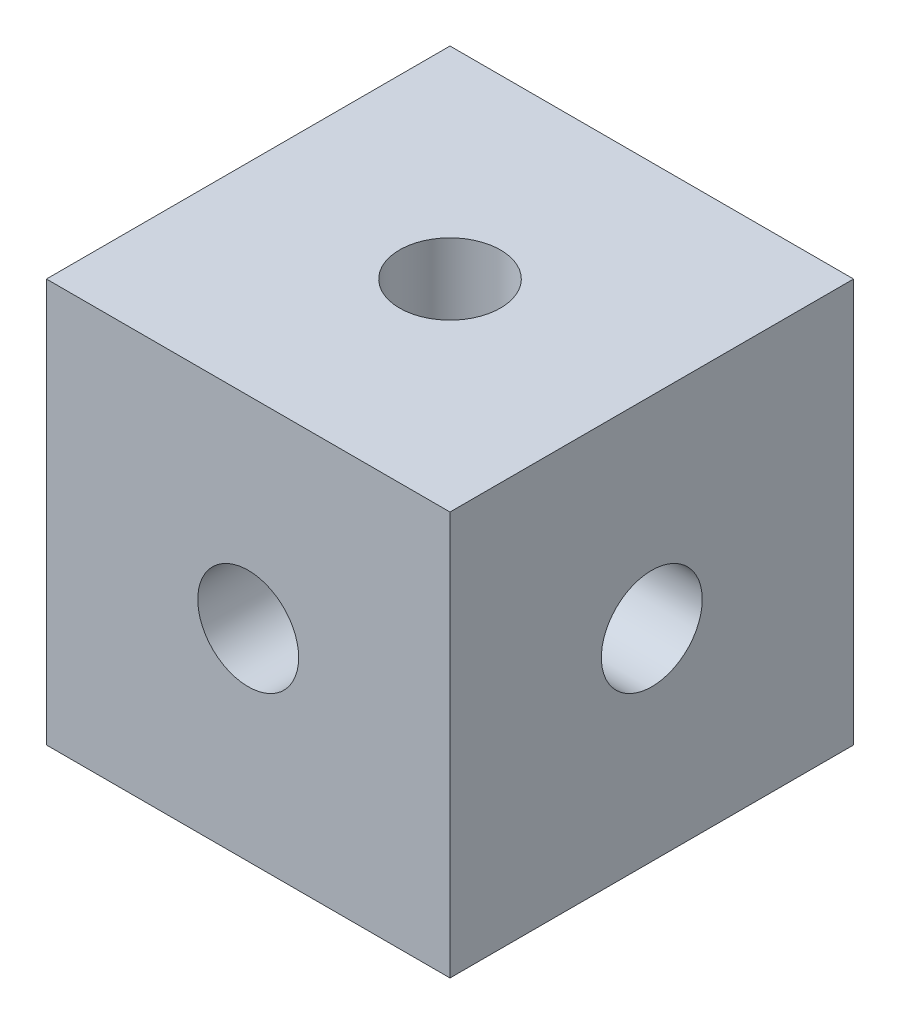
SolidWorks part; units mm, degrees
material "5052-H32"
ref_plane "前视基准面" through (0, 0, 0) normal (0, 0, 1) x (1, 0, 0)
ref_plane "上视基准面" through (0, 0, 0) normal (0, 1, 0) x (1, 0, 0)
ref_plane "右视基准面" through (0, 0, 0) normal (1, 0, 0) x (0, 0, -1)
other "Configuration Table"
sketch "草图1" plane through (0, 0, 0) normal (0, 1, 0) x (1, 0, 0)
  line L1 (-5, 5) -> (5, 5)
  line L2 (-5, 5) -> (-5, -5)
  line L3 (-5, -5) -> (5, -5)
  line L4 (5, 5) -> (5, -5)
  line L5 (-5, 5) -> (5, -5) construction
  line L6 (-5, -5) -> (5, 5) construction
  point P0 (0, 0)
  dimension "D1" = 10
extrude "凸台-拉伸1" add sketch "草图1" along normal mid plane 10
hole_wizard " 螺纹孔1" positions "草图2" profile "草图3" tap size "M3" standard "GB" end condition through all
sketch "草图2" plane through (0, 5, 0) normal (0, 1, 0) x (1, 0, 0)
  point P0 (0, 0)
sketch "草图3" plane through (0, 5, 0) normal (1, 0, 0) x (0, 0, 1)
  line L0 (0, 0) -> (0, 10)
  line L1 (0, 10) -> (1.25, 10)
  line L2 (1.25, 10) -> (1.25, 0)
  line L5 (1.25, 0) -> (0, 0)
  line L11 (0, -6.35) -> (0, 107.95) construction
  dimension "通孔螺纹孔钻头直径" = 2.5
  dimension "通孔螺纹孔钻头深度" = 10
cosmetic thread "孔螺蚊线1" parameters "D2"=3
hole_wizard " 螺纹孔2" positions "草图4" profile "草图5" tap size "M3" standard "GB" end condition through all
sketch "草图4" plane through (5, 0, 0) normal (1, 0, 0) x (0, 0, -1)
  point P0 (0, 0)
sketch "草图5" plane through (5, 0, 0) normal (0, 1, 0) x (0, 0, -1)
  line L0 (0, 0) -> (0, 10)
  line L1 (0, 10) -> (1.25, 10)
  line L2 (1.25, 10) -> (1.25, 0)
  line L5 (1.25, 0) -> (0, 0)
  line L11 (0, -6.35) -> (0, 107.95) construction
  dimension "通孔螺纹孔钻头直径" = 2.5
  dimension "通孔螺纹孔钻头深度" = 10
cosmetic thread "孔螺蚊线2" parameters "D2"=3
hole_wizard " 螺纹孔3" positions "草图6" profile "草图7" tap size "M3" standard "GB" end condition through all
sketch "草图6" plane through (0, 0, 5) normal (0, 0, 1) x (1, 0, 0)
  point P0 (0, 0)
sketch "草图7" plane through (0, 0, 5) normal (1, 0, 0) x (0, -1, 0)
  line L0 (0, 0) -> (0, 10)
  line L1 (0, 10) -> (1.25, 10)
  line L2 (1.25, 10) -> (1.25, 0)
  line L5 (1.25, 0) -> (0, 0)
  line L11 (0, -6.35) -> (0, 107.95) construction
  dimension "通孔螺纹孔钻头直径" = 2.5
  dimension "通孔螺纹孔钻头深度" = 10
cosmetic thread "孔螺蚊线3" parameters "D2"=3
sketch "草图8" plane through (0, 0, 5) normal (0, 0, 1) x (1, 0, 0)
  line L0 (0, -11) -> (0, 11) construction
  point P4 (0, 0)
  dimension "D1" = 22
sketch "草图9" [suppressed] plane through (-4, 0, 0) normal (-1, 0, 0) x (0, 0, 1)
  line L0 (0, -6) -> (0, 6) construction
  point P4 (0, 0)
  dimension "D1" = 12
hole_wizard "M3 螺纹孔1" [suppressed] positions "草图10" profile "草图11" tap size "M3" standard "GB"
sketch "草图10" plane through (-4, 0, 0) normal (-1, 0, 0) x (0, 0, 1)
  point P0 (0, 6)
  point P3 (0, -6)
sketch "草图11" plane through (-4, 6, 0) normal (0, 1, 0) x (0, 0, 1)
  line L0 (0, 0) -> (0, 8)
  line L1 (0, 8) -> (1.25, 8)
  line L2 (1.25, 8) -> (1.25, 0)
  line L5 (1.25, 0) -> (0, 0)
  line L11 (0, -6.35) -> (0, 107.95) construction
  dimension "通孔螺纹孔钻头直径" = 2.5
  dimension "通孔螺纹孔钻头深度" = 8
cosmetic thread "孔螺蚊线4" [suppressed] parameters "D2"=3
cosmetic thread "孔螺蚊线5" [suppressed] parameters "D2"=3
hole_wizard "M3 螺纹孔2" [suppressed] positions "草图12" profile "草图13" tap size "M3" standard "GB"
sketch "草图12" plane through (0, 0, 4) normal (0, 0, 1) x (1, 0, 0)
  point P0 (0, 11)
  point P3 (0, -11)
sketch "草图13" plane through (0, 11, 4) normal (1, 0, 0) x (0, -1, 0)
  line L0 (0, 0) -> (0, 8)
  line L1 (0, 8) -> (1.25, 8)
  line L2 (1.25, 8) -> (1.25, 0)
  line L5 (1.25, 0) -> (0, 0)
  line L11 (0, -6.35) -> (0, 107.95) construction
  dimension "通孔螺纹孔钻头直径" = 2.5
  dimension "通孔螺纹孔钻头深度" = 8
cosmetic thread "孔螺蚊线6" [suppressed] parameters "D2"=3
cosmetic thread "孔螺蚊线7" [suppressed] parameters "D2"=3
move or copy body "实体-移动/复制1" [suppressed] bodies to move or copy 109
